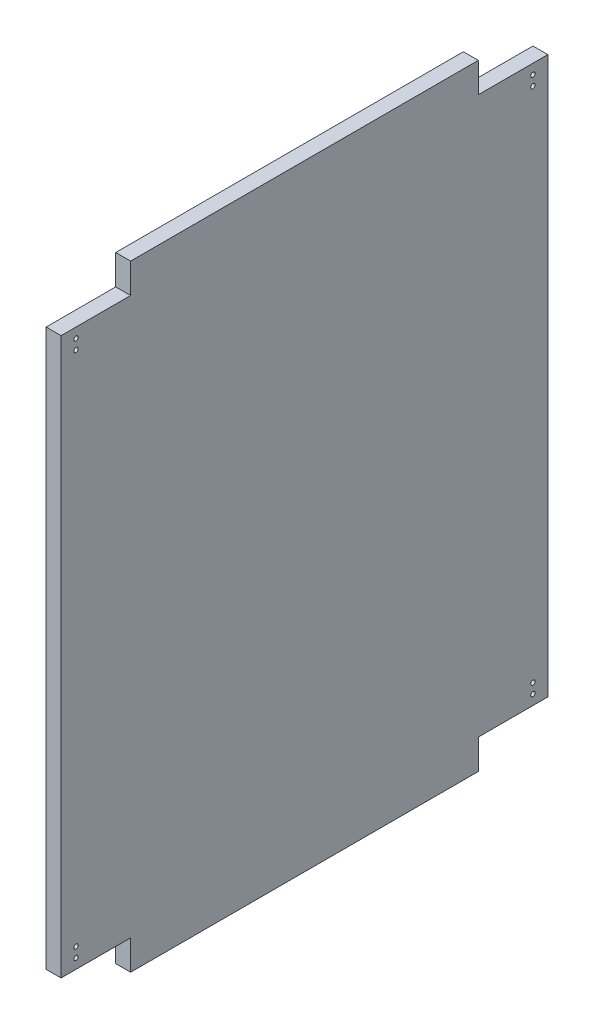
SolidWorks part; units mm, degrees
material "Pine"
ref_plane "Front Plane" through (0, 0, 0) normal (0, 0, 1) x (1, 0, 0)
ref_plane "Top Plane" through (0, 0, 0) normal (0, 1, 0) x (1, 0, 0)
ref_plane "Right Plane" through (0, 0, 0) normal (1, 0, 0) x (0, 0, -1)
sketch "Sketch1" plane through (0, 0, 0) normal (1, 0, 0) x (0, 0, -1)
  line L1 (0, 0) -> (-622.3, 0)
  line L2 (0, 0) -> (0, 787.4)
  line L3 (0, 787.4) -> (-622.3, 787.4)
  line L4 (-622.3, 0) -> (-622.3, 787.4)
  dimension "D1" = 622.3
  dimension "D2" = 787.4
extrude "Boss-Extrude1" add sketch "Sketch1" against normal blind 19.05
sketch "Sketch2" plane through (-19.05, 0, 0) normal (-1, 0, 0) x (0, 0, 1)
  line L1 (0, 787.4) -> (88.9, 787.4)
  line L2 (0, 787.4) -> (0, 749.3)
  line L3 (0, 749.3) -> (88.9, 749.3)
  line L4 (88.9, 787.4) -> (88.9, 749.3)
  line L5 (622.3, 787.4) -> (533.4, 787.4)
  line L6 (622.3, 787.4) -> (622.3, 749.3)
  line L7 (622.3, 749.3) -> (533.4, 749.3)
  line L8 (533.4, 787.4) -> (533.4, 749.3)
  line L9 (622.3, 0) -> (533.4, 0)
  line L10 (622.3, 0) -> (622.3, 38.1)
  line L11 (622.3, 38.1) -> (533.4, 38.1)
  line L12 (533.4, 0) -> (533.4, 38.1)
  line L13 (0, 0) -> (88.9, 0)
  line L14 (0, 0) -> (0, 38.1)
  line L15 (0, 38.1) -> (88.9, 38.1)
  line L16 (88.9, 0) -> (88.9, 38.1)
  dimension "D1" = 88.9
  dimension "D2" = 38.1
extrude "Cut-Extrude1" cut sketch "Sketch2" against normal through all
hole_wizard "#10 Clearance Hole6" positions "Sketch5" profile "Sketch6" hole size "#10" standard "ANSI Inch" end condition through all
sketch "Sketch5" plane through (0, 0, 0) normal (1, 0, 0) x (0, 0, -1)
  line L0 (-603.25, 736.6) -> (-603.25, 723.9) construction
  line L2 (-603.25, 63.5) -> (-603.25, 50.8) construction
  line L4 (-19.05, 736.6) -> (-19.05, 723.9) construction
  line L6 (-19.05, 63.5) -> (-19.05, 50.8) construction
  line L8 (-622.3, 749.3) -> (-622.3, 38.1) construction
  line L9 (-622.3, 38.1) -> (-533.4, 38.1) construction
  line L10 (0, 38.1) -> (0, 749.3) construction
  line L11 (-533.4, 749.3) -> (-622.3, 749.3) construction
  point P0 (-603.25, 50.8)
  point P2 (-603.25, 63.5)
  point P4 (-19.05, 50.8)
  point P6 (-19.05, 63.5)
  point P8 (-19.05, 723.9)
  point P10 (-19.05, 736.6)
  point P12 (-603.25, 723.9)
  point P14 (-603.25, 736.6)
  point P29 (0, 0)
  point P30 (0, 0)
  dimension "D1" = 19.05
  dimension "D2" = 12.7
  dimension "D3" = 12.7
  dimension "D4" = 19.05
  dimension "D5" = 12.7
sketch "Sketch6" plane through (0, 50.8, 603.25) normal (0, 1, 0) x (0, 0, -1)
  line L0 (0, 0) -> (0, 19.05)
  line L1 (0, 19.05) -> (2.8067, 19.05)
  line L2 (2.8067, 19.05) -> (2.8067, 0)
  line L5 (2.8067, 0) -> (0, 0)
  line L11 (0, -6.35) -> (0, 107.95) construction
  dimension "Thru Hole Dia." = 5.6134
  dimension "Thru Hole Depth" = 19.05
ref_plane "Plane1" through (0, 0, 311.15) normal (0, 0, 1) x (1, 0, 0)
ref_plane "Plane2" through (0, 393.7, 0) normal (0, 1, 0) x (1, 0, 0)
